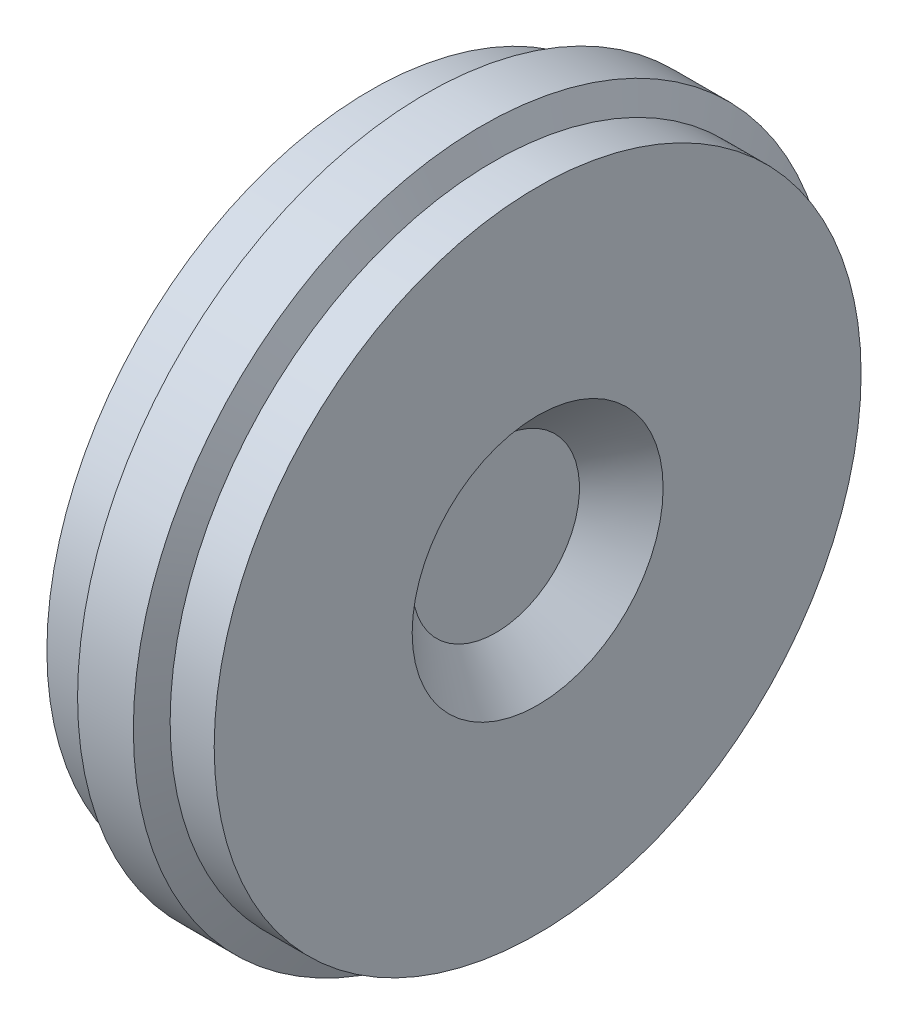
SolidWorks part; units mm, degrees
material "AISI 1020"
ref_plane "Front Plane" through (0, 0, 0) normal (0, 0, 1) x (1, 0, 0)
ref_plane "Top Plane" through (0, 0, 0) normal (0, 1, 0) x (1, 0, 0)
ref_plane "Right Plane" through (0, 0, 0) normal (1, 0, 0) x (0, 0, -1)
sketch "Sketch1" plane through (0, 0, 0) normal (0, 0, 1) x (1, 0, 0)
  line L0 (0, 0) -> (0, 125)
  line L1 (0, 125) -> (-10, 125)
  line L2 (-10, 125) -> (-14.1968, 116)
  line L3 (-14.1968, 116) -> (-30, 116)
  line L4 (-30, 116) -> (-30, 45)
  line L5 (-30, 45) -> (-15, 30)
  line L6 (-15, 30) -> (-15, 0)
  line L7 (-15, 0) -> (0, 0)
  line L8 (0, 0) -> (35.617, 0) construction
  line L9 (0, 0) -> (0, -39.6577) construction
  dimension "D2" = 9
  dimension "D3" = 10
  dimension "D4" = 65
  dimension "D5" = 250
  dimension "D1" = 60
  dimension "D6" = 60
  dimension "D7" = 15
  dimension "D8" = 45
revolve "Revolve1" add sketch "Sketch1" angle 360 about L8
mirror "Mirror1" about plane through (0, 0, 0) normal (-1, 0, 0) of bodies 101
equation "\"A\"=250"
equation "\"D5@Sketch1\"=\"A\""
